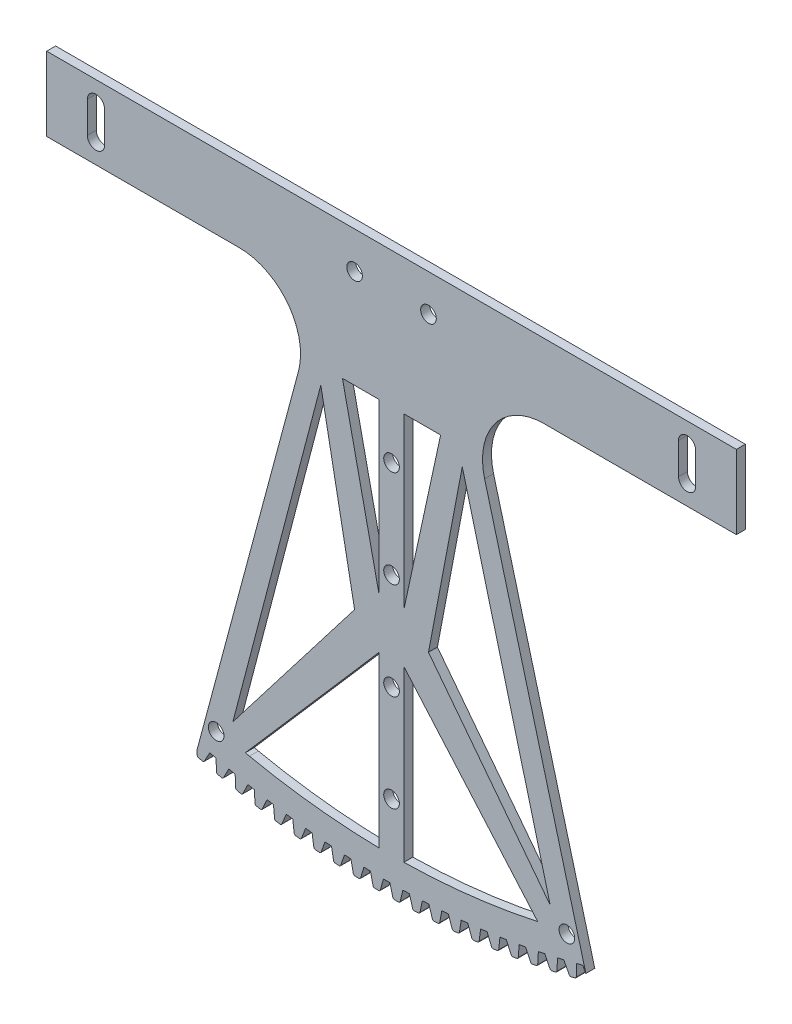
SolidWorks part; units mm, degrees
material "Maple"
ref_plane "Front Plane" through (0, 0, 0) normal (0, 0, 1) x (1, 0, 0)
ref_plane "Top Plane" through (0, 0, 0) normal (0, 1, 0) x (1, 0, 0)
ref_plane "Right Plane" through (0, 0, 0) normal (1, 0, 0) x (0, 0, -1)
sketch "Sketch3" plane through (0, 0, 0) normal (0, 0, 1) x (1, 0, 0)
  line L0 (0, 0) -> (0, -304.8) construction
  line L1 (-21.234, -79.2464) -> (-78.888, -294.4142)
  line L2 (21.234, -79.2464) -> (78.888, -294.4142)
  line L4 (-140, -79.56) -> (140, -79.56)
  line L5 (-140, -79.56) -> (-140, -109.56)
  line L6 (-140, -109.56) -> (140, -109.56)
  line L7 (140, -79.56) -> (140, -109.56)
  line L8 (0, -109.56) -> (0, -79.56) construction
  line L9 (-140, -94.56) -> (140, -94.56) construction
  arc A0 (-78.888, -294.4142) -> (78.888, -294.4142) centre (0, 0) ccw
  point P269 (0, -94.56)
  dimension "D1" = 304.8
  dimension "D4" = 79.56
  dimension "D5" = 30
  dimension "D6" = 280
  dimension "D7" = 140
extrude "Boss-Extrude2" add sketch "Sketch3" along normal blind 3.6286 contours L7 L4 L2 L6 | L1 L6 L2 L4 | L1 L4 L2 | L5 L6 L1 L4 | L1 A0 L2 L6
fillet "Fillet1" radius 25 2 edges at (-29.3565, -109.56, 1.8143) (29.3565, -109.56, 1.8143)
sketch "Sketch4" plane through (0, -79.56, 0) normal (0, 1, 0) x (1, 0, 0)
  line L1 (-140, 0) -> (140, 0)
  line L2 (-140, 0) -> (-140, -3.6286)
  line L3 (-140, -3.6286) -> (140, -3.6286)
  line L4 (140, 0) -> (140, -3.6286)
  line L5 (0, -3.6286) -> (0, 0) construction
  line L6 (-140, -1.8143) -> (140, -1.8143) construction
  point P252 (0, -1.8143)
sketch "Sketch5" plane through (0, 0, 0) normal (0, 0, -1) x (-1, 0, 0)
  line L0 (-123.5, -94.56) -> (-123.5, -100.91)
  line L1 (-116.5, -94.56) -> (-116.5, -100.91)
  line L2 (116.5, -94.56) -> (116.5, -88.21)
  line L3 (140, -79.56) -> (-140, -79.56) construction
  line L4 (-120, -88.21) -> (-120, -100.91) construction
  line L5 (0, -79.56) -> (0, -109.56) construction
  line L6 (-116.5, -94.56) -> (-116.5, -88.21)
  line L7 (-123.5, -94.56) -> (-123.5, -88.21)
  line L8 (116.5, -94.56) -> (116.5, -100.91)
  line L9 (123.5, -94.56) -> (123.5, -100.91)
  line L10 (123.5, -94.56) -> (123.5, -88.21)
  line L11 (-140, -79.56) -> (-140, -109.56) construction
  line L12 (120, -88.21) -> (120, -100.91) construction
  arc A1 (-116.5, -88.21) -> (-123.5, -88.21) centre (-120, -88.21) ccw
  arc A2 (-123.5, -100.91) -> (-116.5, -100.91) centre (-120, -100.91) ccw
  arc A3 (123.5, -100.91) -> (116.5, -100.91) centre (120, -100.91) cw
  arc A4 (116.5, -88.21) -> (123.5, -88.21) centre (120, -88.21) cw
  circle A5 centre (-15, -94.56) radius 3.175
  circle A6 centre (15, -94.56) radius 3.175
  dimension "D1" = 16.5
  dimension "D2" = 7
  dimension "D3" = 8.65
  dimension "D5" = 3.5
  dimension "D6" = 15
  dimension "D8" = 6.35
  dimension "D4" = 6.35
  dimension "D7" = 15
sketch "Sketch13" plane through (0, 0, 0) normal (0, 0, -1) x (-1, 0, 0)
  line L0 (0, 0) -> (78.888, -294.4142)
  line L1 (0, 0) -> (-78.888, -294.4142)
  arc A0 (-78.888, -294.4142) -> (78.888, -294.4142) centre (0, 0) ccw
  arc A1 (-78.888, -294.4142) -> (78.888, -294.4142) centre (0, 0) ccw construction
  arc A2 (-78.888, -294.4142) -> (78.888, -294.4142) centre (0, 0) ccw
  circle A3 centre (0, 0) radius 304.8
  dimension "D1" = 609.6
sketch "Sketch14" plane through (0, 0, 0) normal (0, 0, -1) x (-1, 0, 0)
  line L0 (0, 0) -> (80.0203, -298.6399) construction
  line L2 (78.888, -294.4142) -> (78.9109, -297.0369)
  line L3 (78.9109, -297.0369) -> (76.2891, -297.7211)
  line L18 (76.2891, -297.7211) -> (75.0275, -295.4216)
  line L20 (0, 0) -> (-79.2746, -295.8555) construction
  line L32 (78.888, -294.4142) -> (75.0275, -295.4216)
  line L33 (75.0275, -295.4216) -> (78.888, -294.4142)
  line L34 (0, 0) -> (-75.3952, -296.8678) construction
  line L35 (0, 0) -> (-71.5028, -297.8293) construction
  line L36 (0, 0) -> (-67.5982, -298.7397) construction
  line L37 (0, 0) -> (-63.6821, -299.5989) construction
  line L38 (0, 0) -> (-59.755, -300.4068) construction
  line L39 (0, 0) -> (-55.8176, -301.1633) construction
  line L40 (0, 0) -> (-51.8707, -301.8681) construction
  line L41 (0, 0) -> (-47.9149, -302.5212) construction
  line L42 (0, 0) -> (-43.951, -303.1225) construction
  line L43 (0, 0) -> (-39.9794, -303.6718) construction
  line L44 (0, 0) -> (-36.0011, -304.1691) construction
  line L45 (0, 0) -> (-32.0165, -304.6143) construction
  line L46 (0, 0) -> (-28.0265, -305.0073) construction
  line L47 (0, 0) -> (-24.0316, -305.348) construction
  line L48 (0, 0) -> (-20.0327, -305.6364) construction
  line L49 (0, 0) -> (-16.0303, -305.8724) construction
  line L50 (0, 0) -> (-12.0252, -306.0561) construction
  line L51 (0, 0) -> (-8.018, -306.1873) construction
  line L52 (0, 0) -> (-4.0094, -306.266) construction
  line L53 (0, 0) -> (-0.0002, -306.2922) construction
  line L54 (0, 0) -> (4.0091, -306.266) construction
  line L55 (0, 0) -> (8.0176, -306.1873) construction
  line L56 (0, 0) -> (12.0248, -306.0561) construction
  line L57 (0, 0) -> (16.03, -305.8725) construction
  line L58 (0, 0) -> (20.0323, -305.6364) construction
  line L59 (0, 0) -> (24.0313, -305.348) construction
  line L60 (0, 0) -> (28.0261, -305.0073) construction
  line L61 (0, 0) -> (32.0162, -304.6143) construction
  line L62 (0, 0) -> (36.0007, -304.1691) construction
  line L63 (0, 0) -> (39.9791, -303.6719) construction
  line L64 (0, 0) -> (43.9506, -303.1225) construction
  line L65 (0, 0) -> (47.9146, -302.5213) construction
  line L66 (0, 0) -> (51.8704, -301.8682) construction
  line L67 (0, 0) -> (55.8173, -301.1633) construction
  line L68 (0, 0) -> (59.7546, -300.4069) construction
  line L69 (0, 0) -> (63.6817, -299.599) construction
  line L70 (0, 0) -> (67.5979, -298.7398) construction
  line L71 (0, 0) -> (71.5025, -297.8293) construction
  line L72 (0, 0) -> (75.3948, -296.8679) construction
  line L73 (0, 0) -> (-79.2746, -295.8555) construction
  line L74 (0, 0) -> (-75.3952, -296.8678) construction
  line L137 (37.789, -141.0305) -> (78.888, -294.4142) construction
  line L138 (-140, -79.56) -> (-140, -109.56)
  line L139 (-140, -109.56) -> (-61.9371, -109.56)
  line L140 (-37.789, -141.0305) -> (-78.888, -294.4142)
  line L141 (78.888, -294.4142) -> (37.789, -141.0305)
  line L142 (61.9371, -109.56) -> (140, -109.56)
  line L143 (140, -109.56) -> (140, -79.56)
  line L144 (140, -79.56) -> (-140, -79.56)
  line L145 (-140, -79.56) -> (-140, -109.56)
  line L146 (-140, -109.56) -> (-61.9371, -109.56)
  line L147 (-37.789, -141.0305) -> (-78.888, -294.4142)
  line L149 (61.9371, -109.56) -> (140, -109.56)
  line L150 (140, -109.56) -> (140, -79.56)
  line L151 (140, -79.56) -> (-140, -79.56)
  circle A0 centre (0, 0) radius 307.34
  circle A1 centre (0, 0) radius 302.26
  arc A3 (-37.789, -141.0305) -> (-61.9371, -109.56) centre (-61.9371, -134.56) ccw
  arc A5 (61.9371, -109.56) -> (37.789, -141.0305) centre (61.9371, -134.56) ccw
  arc A6 (-37.789, -141.0305) -> (-61.9371, -109.56) centre (-61.9371, -134.56) ccw
  arc A8 (61.9371, -109.56) -> (37.789, -141.0305) centre (61.9371, -134.56) ccw
  arc A11 (-78.888, -294.4142) -> (78.888, -294.4142) centre (0, 0) ccw
  arc A12 (-78.888, -294.4142) -> (78.888, -294.4142) centre (0, 0) ccw
  dimension "D5" = 614.68
  dimension "D6" = 30
  dimension "D7" = 40
  dimension "D4" = 604.52
  dimension "D1" = 14.5
  dimension "D3" = 14.5
  dimension "D8" = 0.75
  dimension "D9" = 306.2922
  dimension "D10" = 0.75
  dimension "D2" = 0
extrude "Boss-Extrude4" add sketch "Sketch14" against normal up to surface (3.6286 mm away) up to face at (0, -146.6727, 3.6286)
sketch "Sketch15" plane through (0, 0, 0) normal (1, 0, 0) x (0, 0, -1)
  line L0 (0, 0) -> (-23.3364, 0) construction
sketch "Sketch16" plane through (0, 0, 0) normal (0, 0, -1) x (-1, 0, 0)
  line L0 (75.0275, -295.4216) -> (73.7653, -293.1208)
  line L1 (73.7653, -293.1208) -> (71.1999, -293.7544)
  line L2 (71.1999, -293.7544) -> (71.1541, -296.3784)
  line L3 (0, 0) -> (71.5025, -297.8293) construction
  line L4 (0, 0) -> (75.3948, -296.8679) construction
  circle A0 centre (0, 0) radius 302.26 construction
  arc A1 (-78.888, -294.4142) -> (78.888, -294.4142) centre (0, 0) ccw construction
  dimension "D1" = 14.5
  dimension "D2" = 14.5
extrude "Cut-Extrude2" cut sketch "Sketch16" against normal through all and the other way through all
fillet "Fillet2" radius 0.7 2 edges at (-76.2891, -297.7211, 1.8143) (-78.9109, -297.0369, 1.8143)
pattern_circular "CirPattern8" count 20 every 1.5 about axis through (0, 0, 0) along (0, 0, 1) of "Cut-Extrude2", "Boss-Extrude4", "Fillet2"
extrude "Cut-Extrude3" cut sketch "Sketch5" against normal through all
sketch "Sketch17" plane through (0, 0, 0) normal (0, 0, -1) x (-1, 0, 0)
  line L0 (0, -79.56) -> (0, -134.56) construction
  line L1 (140, -79.56) -> (-140, -79.56) construction
  line L2 (-61.9371, -109.56) -> (61.9371, -109.56) construction
  line L3 (-36.9371, -134.56) -> (-26.9371, -134.56) construction
  line L4 (-36.9371, -134.56) -> (-26.9371, -134.56) construction
  line L5 (-26.9371, -134.56) -> (-66.1944, -284.3612) construction
  line L6 (-66.1944, -284.3612) -> (-76.1944, -284.3612) construction
  line L7 (0, -292.2593) -> (5, -292.2593) construction
  line L8 (-37.789, -141.0305) -> (-78.888, -294.4142) construction
  line L9 (0, -134.56) -> (-5, -134.56) construction
  line L10 (0, -134.56) -> (5, -134.56) construction
  line L11 (26.9371, -134.56) -> (36.9371, -134.56) construction
  line L12 (-5, -134.56) -> (-5, -292.2593) construction
  line L13 (36.9371, -134.56) -> (26.9371, -134.56) construction
  line L14 (26.9371, -134.56) -> (66.1944, -284.3612) construction
  line L15 (66.1944, -284.3612) -> (76.1944, -284.3612) construction
  line L16 (37.789, -141.0305) -> (78.888, -294.4142) construction
  line L17 (0.6571, -302.2593) -> (-3.5916, -302.2593) construction
  line L18 (-5, -134.56) -> (5, -134.56) construction
  line L19 (-3.5916, -292.2593) -> (-5, -292.2593) construction
  line L20 (5, -134.56) -> (5, -292.2593) construction
  line L21 (-3.5916, -302.2593) -> (-3.5916, -292.2593) construction
  line L22 (0, -193.6972) -> (0, -233.1221) construction
  line L23 (64.4199, -277.5899) -> (15, -213.4096)
  line L24 (-66.1944, -284.3612) -> (-68.6354, -294.3612) construction
  line L25 (-67.3487, -294.6613) -> (-69.9221, -294.0612) construction
  line L26 (71.1999, -293.7544) -> (66.067, -294.9513) construction
  line L27 (66.1944, -284.3612) -> (68.6335, -294.3529) construction
  line L28 (26.9371, -134.56) -> (66.1944, -284.3612)
  line L29 (26.9371, -134.56) -> (5, -134.56)
  line L30 (5, -134.56) -> (5, -292.2593)
  line L31 (-66.1944, -284.3612) -> (-26.9371, -134.56)
  line L32 (-26.9371, -134.56) -> (-5, -134.56)
  line L33 (-5, -134.56) -> (-5, -292.2593)
  line L34 (15, -213.4096) -> (28.7117, -141.3313)
  line L35 (66.1944, -284.3612) -> (57.6779, -286.2946)
  line L36 (66.1944, -284.3612) -> (64.4199, -277.5899) construction
  line L37 (5, -223.4096) -> (59.3729, -285.9321)
  line L41 (26.9371, -134.56) -> (28.7117, -141.3313) construction
  line L42 (26.9371, -134.56) -> (19.9371, -134.56) construction
  line L44 (28.7117, -141.3313) -> (26.9371, -134.56) construction
  line L47 (5, -203.4096) -> (19.9371, -134.56)
  line L48 (-59.3729, -285.9321) -> (-5, -223.4096)
  line L50 (-64.4199, -277.5899) -> (-15, -213.4096)
  line L51 (-15, -213.4096) -> (-28.7117, -141.3313)
  line L52 (-5, -203.4096) -> (-19.9371, -134.56)
  circle A0 centre (0, -272.5469) radius 3.175
  arc A1 (61.9371, -109.56) -> (37.789, -141.0305) centre (61.9371, -134.56) ccw construction
  arc A2 (-37.789, -141.0305) -> (-61.9371, -109.56) centre (-61.9371, -134.56) ccw construction
  arc A3 (-66.1944, -284.3612) -> (-5, -292.2593) centre (0, -12.5018) ccw
  arc A4 (5, -292.2593) -> (66.1944, -284.3612) centre (0, -12.5018) ccw
  circle A5 centre (0, -233.1221) radius 3.175
  circle A6 centre (0, -193.6972) radius 3.175
  circle A7 centre (0, -154.2724) radius 3.175
  circle A8 centre (-71.1944, -284.3612) radius 3.175
  circle A9 centre (71.1944, -284.3612) radius 3.175
  arc A13 (19.9371, -134.56) -> (28.7117, -141.3313) centre (26.9371, -134.56) ccw construction
  arc A14 (19.9371, -134.56) -> (28.7117, -141.3313) centre (26.9371, -134.56) ccw construction
  arc A15 (-59.3729, -285.9321) -> (-64.4199, -277.5899) centre (-66.1944, -284.3612) ccw construction
  arc A16 (-64.4199, -277.5899) -> (-59.3729, -285.9321) centre (-66.1944, -284.3612) cw
  arc A17 (-5, -203.4096) -> (-5, -223.4096) centre (-5, -213.4096) ccw construction
  arc A18 (-28.7117, -141.3313) -> (-19.9371, -134.56) centre (-26.9371, -134.56) ccw construction
  arc A19 (5, -223.4096) -> (5, -203.4096) centre (5, -213.4096) ccw construction
  arc A20 (64.4199, -277.5899) -> (59.3729, -285.9321) centre (66.1944, -284.3612) ccw construction
  dimension "D13" = 6.35
  dimension "D14" = 6.35
  dimension "D15" = 10
  dimension "D16" = 7
  dimension "D17" = 7
  dimension "D20" = 7
  dimension "D21" = 10
  dimension "D22" = 7
  dimension "D18" = 7
  dimension "D1" = 10
  dimension "D2" = 5
  dimension "D3" = 10
  dimension "D4" = 10
  dimension "D5" = 5
  dimension "D6" = 5
  dimension "D7" = 10
  dimension "D8" = 10
  dimension "D9" = 5
  dimension "D10" = 10
  dimension "D11" = 157.6993
  dimension "D12" = 10
  dimension "D19" = 12.241
extrude "Cut-Extrude4" cut sketch "Sketch17" against normal through all contours L50 L51 L31 | L34 L23 L28 | L30 A4 L35 L37 | L48 A3 L33 | L30 L47 L29 | L52 L33 L32 | A6 | A7 | A5 | A0 | A9 | A8
equation "\"D7@Sketch3\"=\"D6@Sketch3\"/2"
